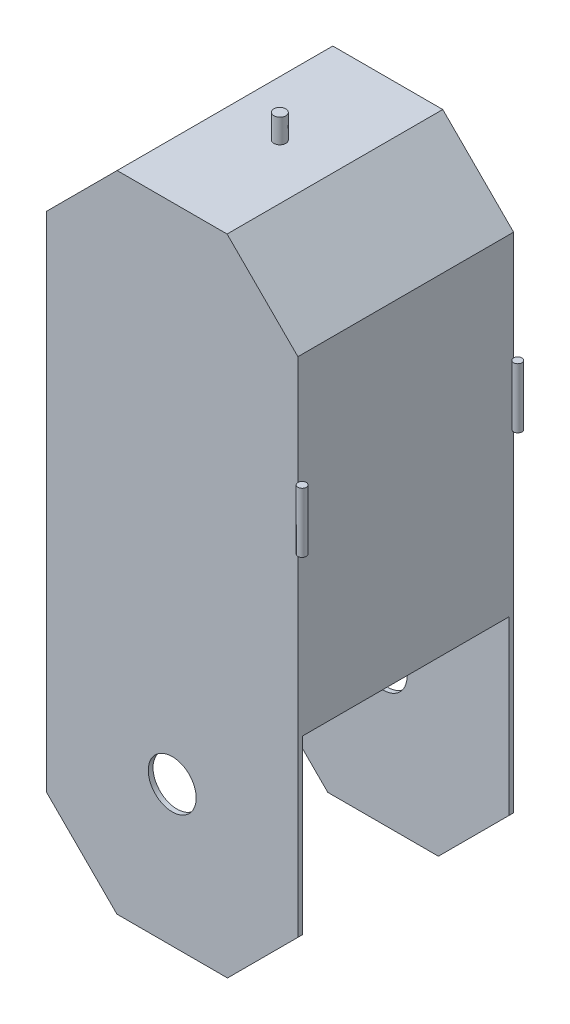
SolidWorks part; units mm, degrees
ref_plane "Спереди" through (0, 0, 0) normal (0, 0, 1) x (1, 0, 0)
ref_plane "Сверху" through (0, 0, 0) normal (0, 1, 0) x (1, 0, 0)
ref_plane "Справа" through (0, 0, 0) normal (1, 0, 0) x (0, 0, -1)
sketch "Эскиз1" plane through (0, 0, 0) normal (0, 0, 1) x (1, 0, 0)
  line L0 (105.0829, 581.7221) -> (45.979, 640.8259)
  line L1 (45.979, 640.8259) -> (-45.8132, 640.8259)
  line L2 (-45.8132, 640.8259) -> (-104.9171, 581.7221)
  line L3 (-104.9171, 581.7221) -> (-104.9171, 162.2129)
  line L4 (-104.9171, 162.2129) -> (-45.9732, 103.269)
  line L5 (-45.9732, 103.269) -> (46.3268, 103.269)
  line L6 (46.3268, 103.269) -> (105.0829, 162.0251)
  line L7 (105.0829, 162.0251) -> (105.0829, 581.7221)
  line L8 (0.0829, 640.8259) -> (0.0829, 703.4762) construction
  dimension "D1" = 105
  dimension "D2" = 105
extrude "Вытянуть1" add sketch "Эскиз1" along normal blind 180
sketch "Sketch1" plane through (105.0829, 0, 0) normal (1, 0, 0) x (0, 0, -1)
  line L0 (-248.5664, 317.269) -> (57.8162, 317.269) construction
  line L1 (-180, 103.269) -> (0, 103.269) construction
  line L2 (-180, 162.0251) -> (-180, 581.7221) construction
  line L3 (-176, 96.7638) -> (-4, 96.7638)
  line L4 (-176, 96.7638) -> (-176, 305.6262)
  line L5 (-176, 305.6262) -> (-4, 305.6262)
  line L6 (-4, 96.7638) -> (-4, 305.6262)
  line L7 (0, 162.0251) -> (0, 581.7221) construction
  dimension "D1" = 214
  dimension "D2" = 4
  dimension "D3" = 4
extrude "Cut-Extrude1" cut sketch "Sketch1" against normal through all
sketch "Sketch2" plane through (0, 0, 0) normal (0, 0, -1) x (-1, 0, 0)
  line L0 (45.9732, 103.269) -> (-46.3268, 103.269) construction
  circle A0 centre (-0.1768, 220.269) radius 20
  dimension "D1" = 117
extrude "Cut-Extrude2" cut sketch "Sketch2" against normal through all
ref_plane "Plane1" through (0, 440.8259, 0) normal (0, 1, 0) x (1, 0, 0)
sketch "Sketch3" plane through (0, 440.8259, 0) normal (0, 1, 0) x (1, 0, 0)
  line L0 (105.0829, 0) -> (156.2592, 51.1763) construction
  line L1 (-104.9171, 0) -> (-157.625, 0) construction
  line L2 (-104.9171, -90) -> (-175.894, -90) construction
  line L3 (105.0829, 0) -> (105.0829, 59.0755) construction
  circle A0 centre (108.5829, 0) radius 3.5
  circle A1 centre (108.5829, -180) radius 3.5
  dimension "D1" = 45
extrude "Boss-Extrude1" add sketch "Sketch3" along normal blind 50 separate body
sketch "Sketch4" plane through (0, 640.8259, 0) normal (0, 1, 0) x (1, 0, 0)
  circle A0 centre (0, -90) radius 5
extrude "Boss-Extrude2" add sketch "Sketch4" along normal blind 20
